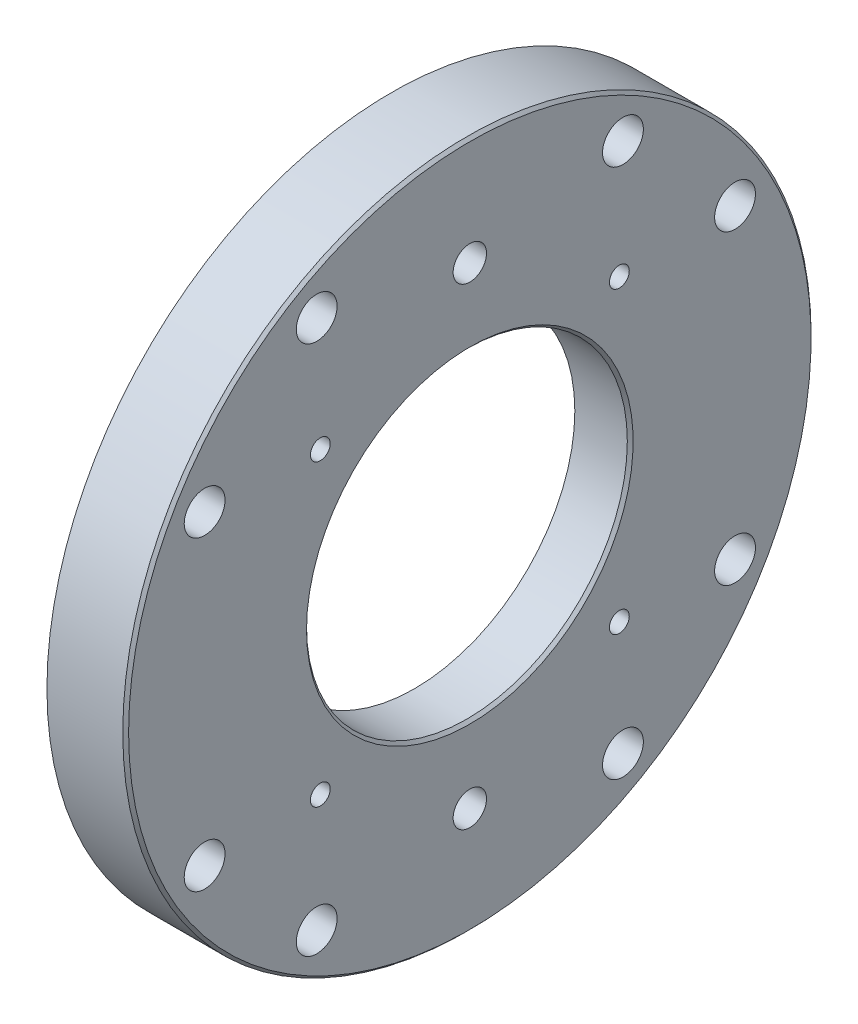
SolidWorks part; units mm, degrees
ref_plane "正面" through (0, 0, 0) normal (0, 0, 1) x (1, 0, 0)
ref_plane "平面" through (0, 0, 0) normal (0, 1, 0) x (1, 0, 0)
ref_plane "右側面" through (0, 0, 0) normal (1, 0, 0) x (0, 0, -1)
sketch "ｽｹｯﾁ1" plane through (0, 0, 0) normal (0, 0, 1) x (1, 0, 0)
  line L0 (0, 117) -> (0, 56)
  line L1 (0, 56) -> (-1, 55)
  line L2 (-1, 55) -> (-19, 55)
  line L3 (-19, 55) -> (-19, 88)
  line L4 (-19, 88) -> (-24, 88)
  line L5 (-24, 88) -> (-24, 115)
  line L6 (-24, 115) -> (-26.5, 115)
  line L7 (-26.5, 115) -> (-27, 115.5)
  line L8 (-27, 115.5) -> (-27, 118)
  line L9 (-27, 118) -> (-1, 118)
  line L10 (-1, 118) -> (0, 117)
  line L11 (-27, 0) -> (0, 0) construction
revolve "回転1" add sketch "ｽｹｯﾁ1" angle 360 about L11
sketch "ｽｹｯﾁ2" plane through (0, 0, 0) normal (1, 0, 0) x (0, 0, -1)
  circle A0 centre (90.9327, 52.5) radius 7
  circle A1 centre (52.5, 90.9327) radius 7
  circle A2 centre (-52.5, 90.9327) radius 7
  circle A3 centre (-90.9327, 52.5) radius 7
  circle A4 centre (-90.9327, -52.5) radius 7
  circle A5 centre (-52.5, -90.9327) radius 7
  circle A6 centre (52.5, -90.9327) radius 7
  circle A7 centre (90.9327, -52.5) radius 7
extrude "ｶｯﾄ - 押し出し1" cut sketch "ｽｹｯﾁ2" against normal through all and the other way through all
sketch "ｽｹｯﾁ3" plane through (0, 0, 0) normal (1, 0, 0) x (0, 0, -1)
  circle A0 centre (51.2652, 51.2652) radius 3.4
  circle A1 centre (-51.2652, 51.2652) radius 3.4
  circle A2 centre (-51.2652, -51.2652) radius 3.4
  circle A3 centre (51.2652, -51.2652) radius 3.4
extrude "ｶｯﾄ - 押し出し2" cut sketch "ｽｹｯﾁ3" against normal through all and the other way through all
sketch "ｽｹｯﾁ4" plane through (0, 0, 0) normal (1, 0, 0) x (0, 0, -1)
  circle A0 centre (0, 81) radius 5.7225
  circle A1 centre (0, -81) radius 5.7225
extrude "ｶｯﾄ - 押し出し3" cut sketch "ｽｹｯﾁ4" against normal through all and the other way through all
